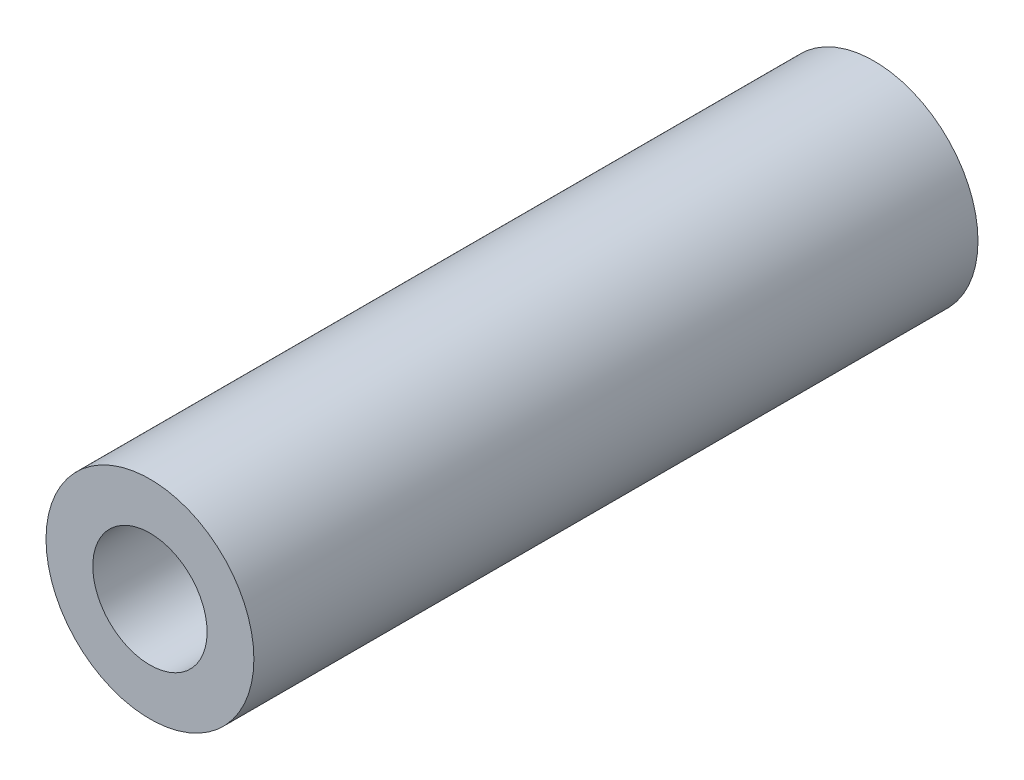
SolidWorks part; units mm, degrees
ref_plane "Front Plane" through (0, 0, 0) normal (0, 0, 1) x (1, 0, 0)
ref_plane "Top Plane" through (0, 0, 0) normal (0, 1, 0) x (1, 0, 0)
ref_plane "Right Plane" through (0, 0, 0) normal (1, 0, 0) x (0, 0, -1)
sketch "Sketch1" plane through (0, 0, 0) normal (0, 0, 1) x (1, 0, 0)
  circle A0 centre (0, 0) radius 6
  dimension "D1" = 12
extrude "Boss-Extrude1" add sketch "Sketch1" along normal blind 41.8
sketch "Sketch2" plane through (0, 0, 41.8) normal (0, 0, 1) x (1, 0, 0)
  point P0 (0, 0)
hole_wizard "M6 Clearance Hole1" positions "Sketch2" profile "Sketch3" hole size "M6" standard "DIN" end condition through all
sketch "Sketch3" plane through (0, 0, 41.8) normal (1, 0, 0) x (0, -1, 0)
  line L0 (0, 0) -> (0, 41.8)
  line L1 (0, 41.8) -> (3.3, 41.8)
  line L2 (3.3, 41.8) -> (3.3, 0)
  line L5 (3.3, 0) -> (0, 0)
  line L11 (0, -6.35) -> (0, 107.95) construction
  dimension "Thru Hole Dia." = 6.6
  dimension "Thru Hole Depth" = 41.8
